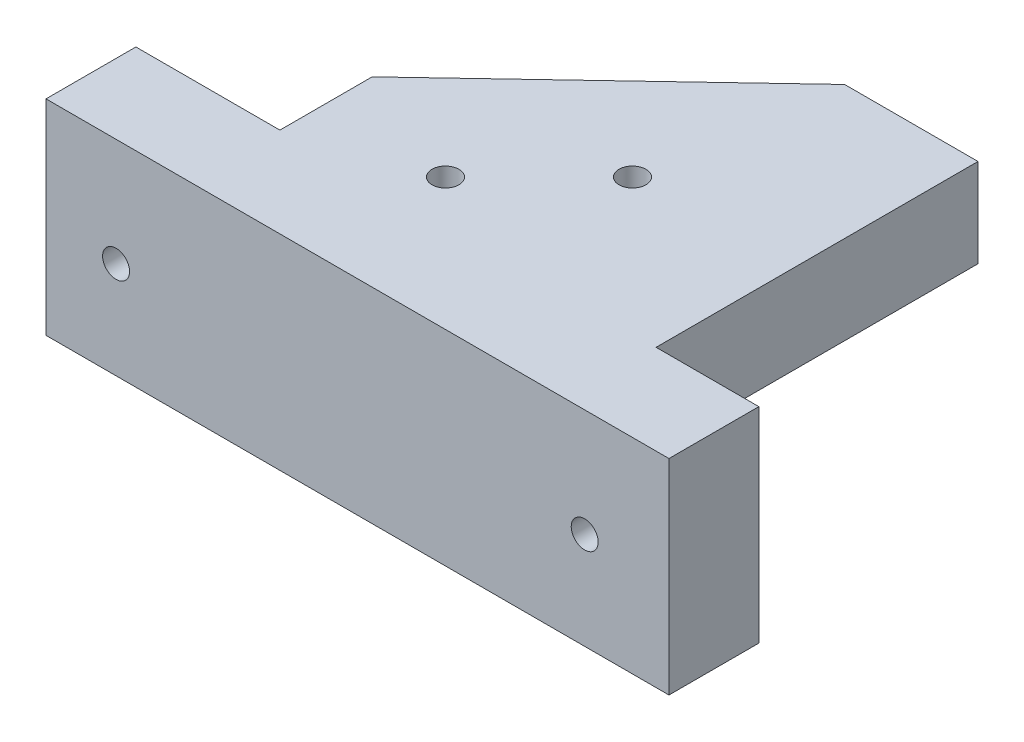
SolidWorks part; units mm, degrees
ref_plane "Front Plane" through (0, 0, 0) normal (0, 0, 1) x (1, 0, 0)
ref_plane "Top Plane" through (0, 0, 0) normal (0, 1, 0) x (1, 0, 0)
ref_plane "Right Plane" through (0, 0, 0) normal (1, 0, 0) x (0, 0, -1)
sketch "Sketch1" plane through (0, 0, 0) normal (0, 0, 1) x (1, 0, 0)
  line L5 (-69.4768, -14.6899) -> (34.4916, -14.6899)
  line L6 (-69.4768, -14.6899) -> (-69.4768, 19.4962)
  line L7 (-69.4768, 19.4962) -> (34.4916, 19.4962)
  line L8 (34.4916, -14.6899) -> (34.4916, 19.4962)
extrude "Boss-Extrude1" add sketch "Sketch1" along normal blind 15
sketch "Sketch2" plane through (0, 0, 0) normal (0, 0, -1) x (-1, 0, 0)
  line L0 (69.4768, 19.4962) -> (69.4768, -14.6899) construction
  line L1 (69.4768, 4.7093) -> (-34.4916, 4.7093)
  line L2 (69.4768, 4.7093) -> (69.4768, 19.4962)
  line L3 (69.4768, 19.4962) -> (-34.4916, 19.4962)
  line L4 (-34.4916, 4.7093) -> (-34.4916, 19.4962)
  line L5 (-34.4916, 19.4962) -> (69.4768, 19.4962) construction
  line L6 (-34.4916, -14.6899) -> (-34.4916, 19.4962) construction
extrude "Boss-Extrude2" add sketch "Sketch2" along normal blind 60
sketch "Sketch3" plane through (0, 4.7093, 0) normal (0, -1, 0) x (1, 0, 0)
  line L0 (-45.4413, 0) -> (-45.4413, -15.4)
  line L1 (-69.4768, 0) -> (34.4916, 0) construction
  line L2 (-45.4413, 0) -> (-45.4413, -15.4) construction
  line L3 (-45.4413, -15.4) -> (-4.9092, -53.7224)
  line L7 (34.4916, 15) -> (34.4916, 0) construction
  line L8 (34.4916, -60) -> (34.4916, 0) construction
  line L9 (34.4916, 0) -> (34.4916, -60)
  line L10 (34.4916, -60) -> (-69.4768, -60) construction
  line L11 (34.4916, -60) -> (-69.4768, -60)
  line L12 (-69.4768, -60) -> (-69.4768, 0)
  line L13 (-69.4768, 0) -> (-45.4413, 0)
  line L20 (34.4916, 0) -> (17.3449, 0)
  line L21 (17.3449, 0) -> (17.3449, -53.7224)
  line L22 (17.3449, -53.7224) -> (-4.9092, -53.7224)
extrude "Cut-Extrude1" cut sketch "Sketch3" against normal through all
hole_wizard "M4 Clearance Hole1" positions "3DSketch2" profile "Sketch4" hole size "M4" standard "ISO" end condition through all
sketch3d "3DSketch2"
  point P0 (-9.2371, 4.7093, -22.6408)
  point P2 (-24.8421, 4.7093, -7.0358)
sketch "Sketch4" plane through (-9.2371, 4.7093, -22.6408) normal (1, 0, 0) x (0, 0, -1)
  line L0 (0, 0) -> (0, 14.7869)
  line L1 (0, 14.7869) -> (2.25, 14.7869)
  line L2 (2.25, 14.7869) -> (2.25, 0)
  line L5 (2.25, 0) -> (0, 0)
  line L11 (0, -6.35) -> (0, 107.95) construction
  dimension "Thru Hole Dia." = 4.5
  dimension "Thru Hole Depth" = 14.7869
hole_wizard "M4 Clearance Hole2" positions "3DSketch3" profile "Sketch5" hole size "M4" standard "ISO" end condition through all
sketch3d "3DSketch3"
  point P0 (-57.7823, 1.4985, 0)
  point P2 (20.4265, 1.4985, 0)
sketch "Sketch5" plane through (-57.7823, 1.4985, 0) normal (1, 0, 0) x (0, 1, 0)
  line L0 (0, 0) -> (0, 15)
  line L1 (0, 15) -> (2.25, 15)
  line L2 (2.25, 15) -> (2.25, 0)
  line L5 (2.25, 0) -> (0, 0)
  line L11 (0, -6.35) -> (0, 107.95) construction
  dimension "Thru Hole Dia." = 4.5
  dimension "Thru Hole Depth" = 15
